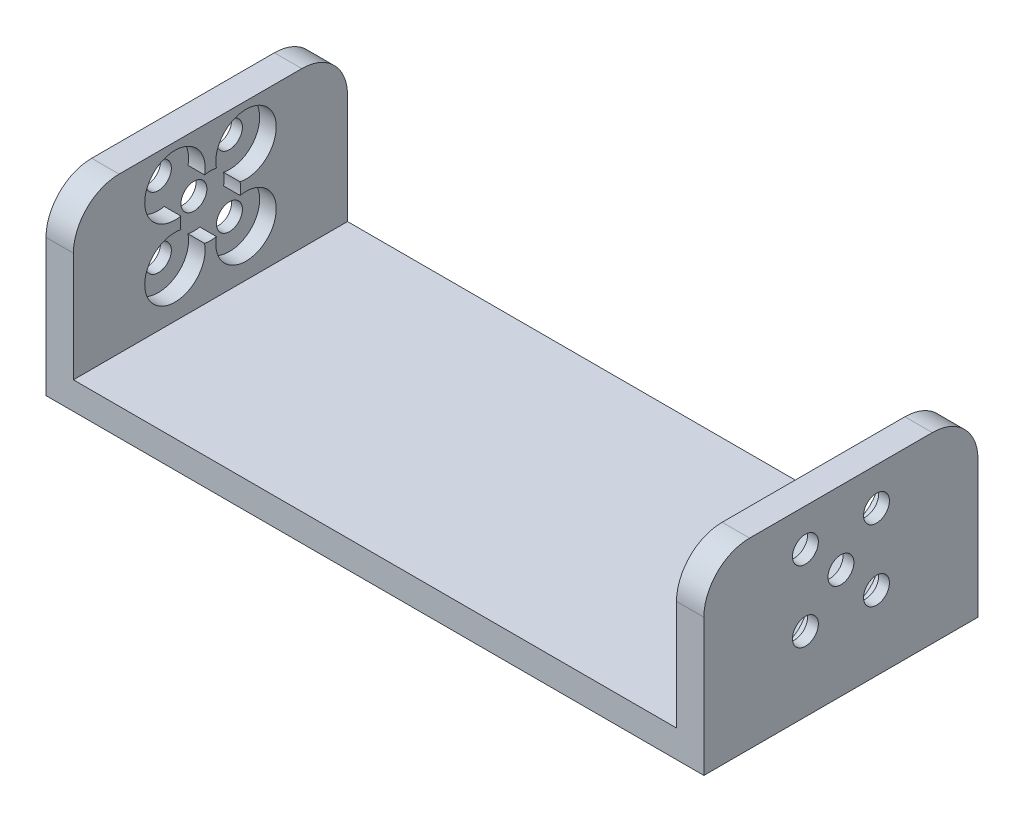
SolidWorks part; units mm, degrees
ref_plane "Front Plane" through (0, 0, 0) normal (0, 0, 1) x (1, 0, 0)
ref_plane "Top Plane" through (0, 0, 0) normal (0, 1, 0) x (1, 0, 0)
ref_plane "Right Plane" through (0, 0, 0) normal (1, 0, 0) x (0, 0, -1)
sketch "Sketch1" plane through (0, 0, 0) normal (0, 1, 0) x (1, 0, 0)
  line L1 (-45.72, 19.05) -> (45.72, 19.05)
  line L2 (-45.72, 19.05) -> (-45.72, -19.05)
  line L3 (-45.72, -19.05) -> (45.72, -19.05)
  line L4 (45.72, 19.05) -> (45.72, -19.05)
  line L5 (-45.72, 19.05) -> (45.72, -19.05) construction
  line L6 (-45.72, -19.05) -> (45.72, 19.05) construction
  point P0 (0, 0)
  dimension "D1" = 91.44
  dimension "D2" = 38.1
extrude "Boss-Extrude1" add sketch "Sketch1" along normal blind 3.81
sketch "Sketch2" plane through (-45.72, 0, 0) normal (-1, 0, 0) x (0, 0, 1)
  line L1 (-19.05, 0) -> (19.05, 0)
  line L2 (-19.05, 0) -> (-19.05, 25.4)
  line L3 (-19.05, 25.4) -> (19.05, 25.4)
  line L4 (19.05, 0) -> (19.05, 25.4)
  dimension "D1" = 25.4
extrude "Boss-Extrude2" add sketch "Sketch2" against normal blind 3.81
sketch "Sketch3" plane through (-45.72, 0, 0) normal (-1, 0, 0) x (0, 0, 1)
  line L0 (0, 0) -> (0, 25.4) construction
  line L1 (19.05, 25.4) -> (-19.05, 25.4) construction
  line L3 (-4.9391, 10.3009) -> (4.9391, 10.3009) construction
  line L4 (-4.9391, 10.3009) -> (-4.9391, 20.1791) construction
  line L5 (-4.9391, 20.1791) -> (4.9391, 20.1791) construction
  line L6 (4.9391, 10.3009) -> (4.9391, 20.1791) construction
  line L7 (-4.9391, 10.3009) -> (4.9391, 20.1791) construction
  line L8 (-4.9391, 20.1791) -> (4.9391, 10.3009) construction
  circle A0 centre (0, 15.24) radius 6.985 construction
  dimension "D2" = 13.97
  dimension "D1" = 10.16
hole_wizard "CBORE for M3 Hex Head Machine Screw1" positions "Sketch4" profile "Sketch5" counterbore size "M3" standard "ANSI Metric"
sketch "Sketch4" plane through (-41.91, 0, 0) normal (1, 0, 0) x (0, 0, -1)
  point P0 (-4.9391, 20.1791)
  point P3 (4.9391, 20.1791)
  point P6 (0, 15.24)
  point P9 (-4.9391, 10.3009)
  point P12 (4.9391, 10.3009)
sketch "Sketch5" plane through (-41.91, 20.1791, 4.9391) normal (0, 1, 0) x (0, 0, -1)
  line L0 (0, 0) -> (0, 3.81)
  line L1 (0, 3.81) -> (1.8, 3.81)
  line L3 (1.8, 3.81) -> (1.8, 2.3)
  line L4 (1.8, 2.3) -> (4.2, 2.3)
  line L5 (4.2, 2.3) -> (4.2, 0)
  line L7 (4.2, 0) -> (0, 0)
  line L11 (0, -6.35) -> (0, 107.95) construction
  dimension "Thru Hole Dia." = 3.6
  dimension "Thru Hole Depth" = 3.81
  dimension "C'Bore Dia." = 8.4
  dimension "C'Bore Depth" = 2.3
fillet "Fillet1" radius 6.35 2 edges at (-43.815, 25.4, -19.05) (-43.815, 25.4, 19.05)
mirror "Mirror1" about plane through (0, 0, 0) normal (1, 0, 0) of "CBORE for M3 Hex Head Machine Screw1", "Boss-Extrude2", "Fillet1"
hole_wizard "CBORE for M2.5 Hex Head Machine Screw2" positions "Sketch6" profile "Sketch7" counterbore size "M2.5" standard "ANSI Metric"
sketch "Sketch6" plane through (36.576, 0, 0) normal (-1, 0, 0) x (0, 0, 1)
  point P0 (0, 15.24)
sketch "Sketch7" plane through (36.576, 15.24, 0) normal (0, 1, 0) x (0, 0, 1)
  line L0 (0, 0) -> (0, 3.81)
  line L1 (0, 3.81) -> (1.55, 3.81)
  line L3 (1.55, 3.81) -> (1.55, 2.1)
  line L4 (1.55, 2.1) -> (3.64, 2.1)
  line L5 (3.64, 2.1) -> (3.64, 0)
  line L7 (3.64, 0) -> (0, 0)
  line L11 (0, -6.35) -> (0, 107.95) construction
  dimension "Thru Hole Dia." = 3.1
  dimension "Thru Hole Depth" = 3.81
  dimension "C'Bore Dia." = 7.28
  dimension "C'Bore Depth" = 2.1
